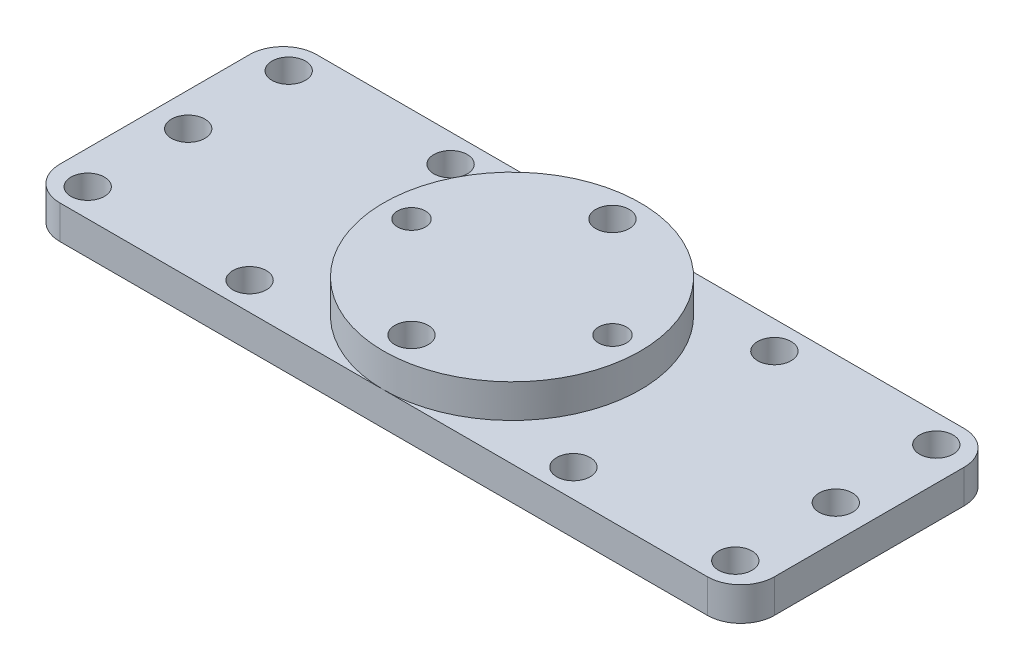
SolidWorks part; units mm, degrees
material "AISI 1020"
ref_plane "Front Plane" through (0, 0, 0) normal (0, 0, 1) x (1, 0, 0)
ref_plane "Top Plane" through (0, 0, 0) normal (0, 1, 0) x (1, 0, 0)
ref_plane "Right Plane" through (0, 0, 0) normal (1, 0, 0) x (0, 0, -1)
sketch "Sketch1" plane through (0, 0, 0) normal (0, 1, 0) x (1, 0, 0)
  line L1 (-32, -11.5) -> (32, -11.5)
  line L2 (-32, -11.5) -> (-32, 11.5)
  line L3 (-32, 11.5) -> (32, 11.5)
  line L4 (32, -11.5) -> (32, 11.5)
  line L5 (-32, -11.5) -> (32, 11.5) construction
  line L6 (-32, 11.5) -> (32, -11.5) construction
  point P0 (0, 0)
  point P6 (-29, 0)
  point P7 (-29, 9)
  point P8 (-14.5, 9)
  point P9 (-14.5, -9)
  point P10 (-29, -9)
  dimension "D1" = 32
  dimension "D2" = 11.5
  dimension "D3" = 9
  dimension "D4" = 9
  dimension "D5" = 14.5
  dimension "D6" = 14.5
extrude "Boss-Extrude1" add sketch "Sketch1" against normal blind 3
sketch "Sketch4" plane through (0, 0, 0) normal (0, 1, 0) x (1, 0, 0)
  point P0 (-29, 0)
  point P3 (-29, 9)
  point P6 (-14.5, 9)
  point P9 (-14.5, -9)
  point P12 (-29, -9)
hole_wizard "Ø3.0 (3) Diameter Hole1" positions "Sketch4" profile "Sketch3" hole size "Ø3.0" standard "ANSI Metric" end condition up to next
sketch "Sketch3" plane through (-29, 0, 0) normal (1, 0, 0) x (0, 0, 1)
  line L0 (0, 0) -> (0, 3)
  line L1 (0, 3) -> (1.5, 3)
  line L2 (1.5, 3) -> (1.5, 0)
  line L5 (1.5, 0) -> (0, 0)
  line L11 (0, -6.35) -> (0, 107.95) construction
  dimension "Thru Hole Dia." = 3
  dimension "Thru Hole Depth" = 3
mirror "Mirror1" about plane through (0, 0, 0) normal (1, 0, 0) of "Ø3.0 (3) Diameter Hole1"
fillet "Fillet1" radius 3 4 edges at (-32, -1.5, -11.5) (32, -1.5, -11.5) (32, -1.5, 11.5) (-32, -1.5, 11.5)
sketch "Sketch5" plane through (0, 0, 0) normal (0, 1, 0) x (1, 0, 0)
  circle A0 centre (0, 0) radius 11.5
  dimension "D1" = 23
extrude "Boss-Extrude2" add sketch "Sketch5" along normal blind 3
sketch "Sketch8" plane through (0, 3, 0) normal (0, 1, 0) x (1, 0, 0)
  point P0 (0, 9)
  point P2 (0, -9)
  dimension "D1" = 9
  dimension "D2" = 9
hole_wizard "Ø3.0 (3) Diameter Hole2" positions "Sketch8" profile "Sketch7" hole size "Ø3.0" standard "ANSI Metric" end condition up to next
sketch "Sketch7" plane through (0, 3, -9) normal (1, 0, 0) x (0, 0, 1)
  line L0 (0, 0) -> (0, 6)
  line L1 (0, 6) -> (1.5, 6)
  line L2 (1.5, 6) -> (1.5, 0)
  line L5 (1.5, 0) -> (0, 0)
  line L11 (0, -6.35) -> (0, 107.95) construction
  dimension "Thru Hole Dia." = 3
  dimension "Thru Hole Depth" = 6
sketch "Sketch11" plane through (0, 3, 0) normal (0, 1, 0) x (1, 0, 0)
  point P0 (-9, 0)
  point P2 (9, 0)
  dimension "D1" = 9
  dimension "D2" = 9
hole_wizard "M3x0.5 Tapped Hole1" positions "Sketch11" profile "Sketch10" tap size "M3x0.5" standard "ANSI Metric"
sketch "Sketch10" plane through (-9, 3, 0) normal (1, 0, 0) x (0, 0, 1)
  line L0 (0, 0) -> (0, 5.5)
  line L1 (0, 5.5) -> (1.25, 4.7489)
  line L2 (1.25, 4.7489) -> (1.25, 0)
  line L5 (1.25, 0) -> (0, 0)
  line L10 (0, 5.5) -> (-1.25, 4.7489) construction
  line L11 (0, -6.35) -> (0, 107.95) construction
  dimension "Tap Drill Dia." = 2.5
  dimension "Tap Drill Depth" = 5.5
  dimension "Drill Angle" = 118
cosmetic thread "Hole Thread1" parameters "D1"=4, "D2"=3
cosmetic thread "Hole Thread2" parameters "D1"=4, "D2"=3
